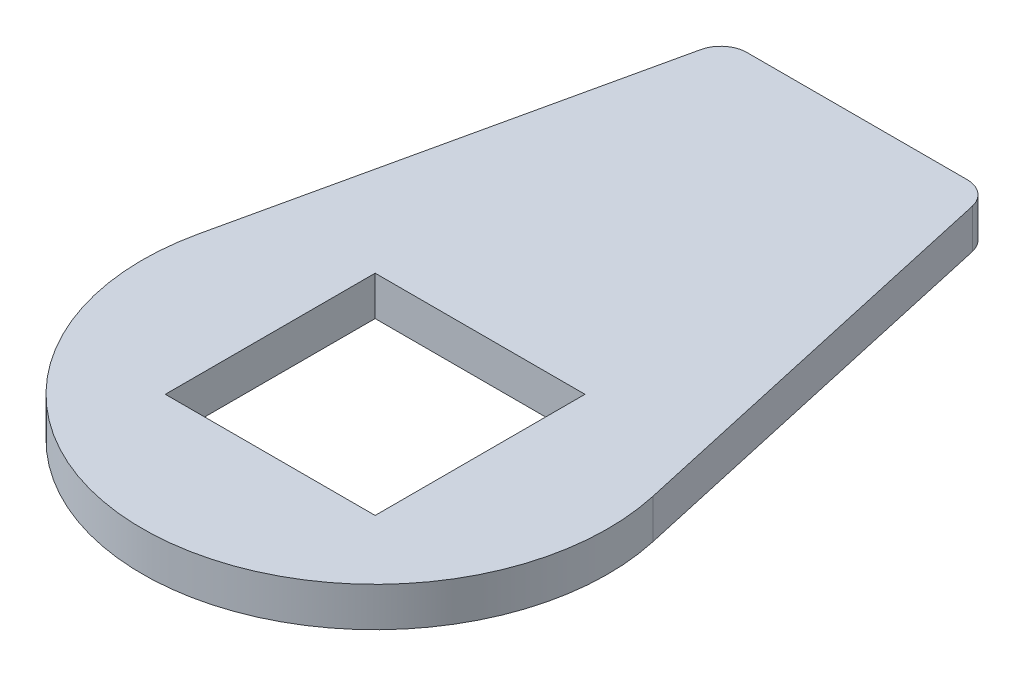
SolidWorks part; units mm, degrees
material "ASTM A36 Steel"
ref_plane "Front Plane" through (0, 0, 0) normal (0, 0, 1) x (1, 0, 0)
ref_plane "Top Plane" through (0, 0, 0) normal (0, 1, 0) x (1, 0, 0)
ref_plane "Right Plane" through (0, 0, 0) normal (1, 0, 0) x (0, 0, -1)
sketch "Sketch1" plane through (0, 0, 0) normal (0, 1, 0) x (1, 0, 0)
  line L1 (-8.3964, 36.75) -> (8.3964, 36.75)
  line L2 (-10.3486, 35.1848) -> (-17.3255, 3.8587)
  line L3 (10.3486, 35.1848) -> (17.3255, 3.8587)
  arc A0 (-17.3255, 3.8587) -> (17.3255, 3.8587) centre (0, 0) ccw
  arc A1 (10.3486, 35.1848) -> (8.3964, 36.75) centre (8.3964, 34.75) ccw
  arc A2 (-8.3964, 36.75) -> (-10.3486, 35.1848) centre (-8.3964, 34.75) ccw
  point P5 (10, 36.75)
  point P8 (0, 36.75)
  point P12 (-10, 36.75)
  dimension "D1" = 20
  dimension "D2" = 35.5
  dimension "D3" = 2
extrude "Boss-Extrude1" add sketch "Sketch1" along normal blind 3
sketch "Sketch2" plane through (0, 3, 0) normal (0, 1, 0) x (1, 0, 0)
  line L1 (-8, -8) -> (8, -8)
  line L2 (-8, -8) -> (-8, 8)
  line L3 (-8, 8) -> (8, 8)
  line L4 (8, -8) -> (8, 8)
  line L5 (-8, -8) -> (8, 8) construction
  line L6 (-8, 8) -> (8, -8) construction
  point P0 (0, 0)
extrude "Cut-Extrude1" cut sketch "Sketch2" against normal blind 3
